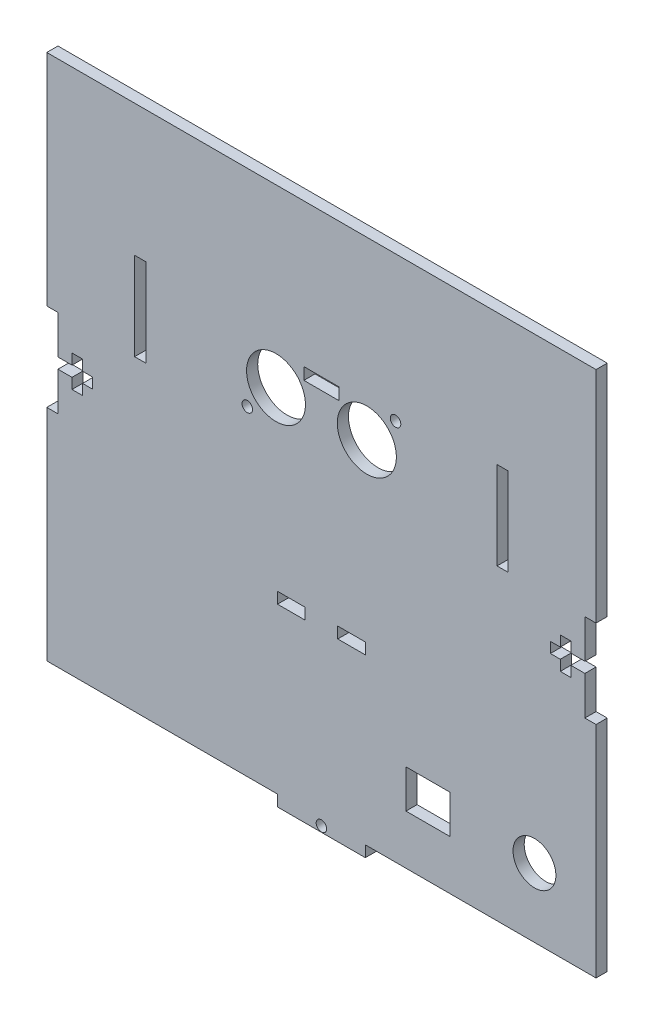
SolidWorks part; units mm, degrees
ref_plane "Front Plane" through (0, 0, 0) normal (0, 0, 1) x (1, 0, 0)
ref_plane "Top Plane" through (0, 0, 0) normal (0, 1, 0) x (1, 0, 0)
ref_plane "Right Plane" through (0, 0, 0) normal (1, 0, 0) x (0, 0, -1)
sketch "Sketch1" plane through (0, 0, 0) normal (0, 0, 1) x (1, 0, 0)
  line L0 (-12.5, 25) -> (12.5, 25) construction
  line L1 (-78.18, 75) -> (78.18, 75)
  line L2 (-78.18, 75) -> (-78.18, 12.5)
  line L3 (-78.18, -75) -> (-12.5, -75)
  line L4 (78.18, 75) -> (78.18, 12.5)
  line L5 (-78.18, 75) -> (78.18, -75) construction
  line L6 (-78.18, -75) -> (78.18, 75) construction
  line L25 (0, 75) -> (0, -75) construction
  line L26 (-100, 0) -> (100, 0) construction
  line L27 (-75, -1.5) -> (-75, -12.5)
  line L28 (-75, 12.5) -> (-78.18, 12.5)
  line L29 (-75, 12.5) -> (-75, 1.5)
  line L30 (-75, -12.5) -> (-78.18, -12.5)
  line L32 (-75, 12.5) -> (-78.18, -12.5) construction
  line L33 (-75, -12.5) -> (-78.18, 12.5) construction
  line L34 (-65.18, 1.5) -> (-68, 1.5)
  line L35 (-65.18, 1.5) -> (-65.18, -1.5)
  line L36 (-65.18, -1.5) -> (-68, -1.5)
  line L38 (-65.18, 1.5) -> (-75, -1.5) construction
  line L39 (-65.18, -1.5) -> (-75, 1.5) construction
  line L44 (-71, 4.5) -> (-68, 4.5)
  line L45 (-71, 4.5) -> (-71, 1.5)
  line L46 (-71, -4.5) -> (-68, -4.5)
  line L47 (-68, 4.5) -> (-68, 1.5)
  line L48 (-71, 4.5) -> (-68, -4.5) construction
  line L49 (-71, -4.5) -> (-68, 4.5) construction
  line L50 (-71, -1.5) -> (-71, -4.5)
  line L51 (-68, -1.5) -> (-68, -4.5)
  line L52 (-71, 1.5) -> (-75, 1.5)
  line L53 (-71, -1.5) -> (-75, -1.5)
  line L54 (65.18, 1.5) -> (68, 1.5)
  line L55 (68, 4.5) -> (68, 1.5)
  line L56 (71, 4.5) -> (68, 4.5)
  line L57 (71, 4.5) -> (71, 1.5)
  line L58 (71, 1.5) -> (75, 1.5)
  line L59 (75, 12.5) -> (75, 1.5)
  line L60 (75, 12.5) -> (78.18, 12.5)
  line L62 (75, -12.5) -> (78.18, -12.5)
  line L63 (75, -1.5) -> (75, -12.5)
  line L64 (71, -1.5) -> (75, -1.5)
  line L65 (71, -1.5) -> (71, -4.5)
  line L66 (71, -4.5) -> (68, -4.5)
  line L67 (68, -1.5) -> (68, -4.5)
  line L68 (65.18, -1.5) -> (68, -1.5)
  line L69 (65.18, 1.5) -> (65.18, -1.5)
  line L70 (-78.18, -12.5) -> (-78.18, -75)
  line L71 (78.18, -12.5) -> (78.18, -75)
  line L72 (0, -78.18) -> (0, -75) construction
  line L74 (12.5, -75) -> (12.5, -78.18)
  line L75 (12.5, -78.18) -> (-12.5, -78.18)
  line L76 (-12.5, -75) -> (-12.5, -78.18)
  line L77 (12.5, -76.59) -> (-12.5, -76.59) construction
  line L78 (12.5, -75) -> (78.18, -75)
  circle A2 centre (0, -76.59) radius 1.5
  point P0 (0, 0)
  point P6 (-51.6, 50)
  point P11 (51.6, 50)
  point P16 (0, 0)
  point P17 (0, -1.6)
  point P27 (0, 25)
  point P30 (-76.59, 0)
  point P35 (-70.09, 0)
  point P40 (-70.09, 0)
  point P41 (-69.5, 0)
  dimension "D13" = 25
  dimension "D23" = 3
  dimension "D1" = 150
  dimension "D2" = 156.36
  dimension "D3" = 9
  dimension "D14" = 50
  dimension "D15" = 25
  dimension "D16" = 13
  dimension "D17" = 3.18
  dimension "D18" = 3
  dimension "D19" = 4
  dimension "D20" = 3
  dimension "D21" = 3.18
  dimension "D22" = 25
extrude "Boss-Extrude1" add sketch "Sketch1" along normal blind 3.18
sketch "Sketch2" plane through (0, 0, 3.18) normal (0, 0, 1) x (1, 0, 0)
  line L0 (30.3478, -50.2) -> (30.3478, -60.7) construction
  line L1 (24.8478, -50.2) -> (35.8478, -50.2) construction
  line L2 (35.8478, -60.7) -> (24.8478, -60.7) construction
  line L3 (24.3478, -55.45) -> (36.3478, -55.45) construction
  line L4 (24.3478, -60.2) -> (24.3478, -50.7) construction
  line L5 (36.3478, -50.7) -> (36.3478, -60.2) construction
  line L7 (24.0625, -49.9909) -> (36.633, -49.9909)
  line L8 (24.0625, -49.9909) -> (24.0625, -60.9091)
  line L9 (24.0625, -60.9091) -> (36.633, -60.9091)
  line L10 (36.633, -49.9909) -> (36.633, -60.9091)
  line L11 (24.0625, -49.9909) -> (36.633, -60.9091) construction
  line L12 (24.0625, -60.9091) -> (36.633, -49.9909) construction
  circle A0 centre (60.6478, -55.45) radius 6.1
  point P12 (30.3478, -55.45)
  dimension "D1" = 12.5705
  dimension "D2" = 10.9182
extrude "Cut-Extrude1" cut sketch "Sketch2" against normal blind 20
sketch "Sketch4" plane through (0, 0, 3.18) normal (0, 0, 1) x (1, 0, 0)
  line L0 (-4.9962, 32.45) -> (-4.9962, 34.25) construction
  line L1 (-4.9962, 34.25) -> (-3.1962, 34.25) construction
  line L2 (3.2038, 30.65) -> (5.0038, 30.65) construction
  line L3 (5.0038, 30.65) -> (5.0038, 32.45) construction
  line L4 (-4.9962, 34.25) -> (-4.9958, 34.15) construction
  line L5 (5.0038, 30.65) -> (5.0035, 30.75) construction
  line L7 (5.0035, 30.75) -> (-4.9958, 30.75)
  line L8 (5.0035, 30.75) -> (5.0035, 34.15)
  line L9 (5.0035, 34.15) -> (-4.9958, 34.15)
  line L10 (-4.9958, 30.75) -> (-4.9958, 34.15)
  circle A0 centre (-12.93, 25) radius 8.385
  circle A1 centre (12.93, 25) radius 8.4104
  arc A2 (-3.1962, 34.25) -> (-3.1962, 30.65) centre (-3.1962, 32.45) ccw construction
  arc A3 (3.2038, 30.65) -> (3.2038, 34.25) centre (3.2038, 32.45) ccw construction
  dimension "D1" = 0.1
  dimension "D2" = 0.1
extrude "Cut-Extrude2" cut sketch "Sketch4" against normal blind 10
sketch "Sketch5" plane through (0, 0, 0) normal (0, 0, -1) x (-1, 0, 0)
  line L0 (12.5, -25) -> (-12.5, -28.18) construction
  line L1 (50, 12.5) -> (53.18, 12.5)
  line L2 (50, 12.5) -> (50, 37.5)
  line L3 (50, 37.5) -> (53.18, 37.5)
  line L4 (53.18, 12.5) -> (53.18, 37.5)
  line L5 (-12.5, -28.18) -> (-4.65, -28.18)
  line L6 (-12.5, -28.18) -> (-12.5, -25)
  line L7 (-12.5, -25) -> (-4.65, -25)
  line L8 (12.5, -28.18) -> (12.5, -25)
  line L9 (-53.18, 12.5) -> (-50, 12.5)
  line L10 (-53.18, 12.5) -> (-53.18, 37.5)
  line L11 (-53.18, 37.5) -> (-50, 37.5)
  line L12 (-50, 12.5) -> (-50, 37.5)
  line L13 (12.5, -28.18) -> (-12.5, -25) construction
  line L14 (4.65, -28.18) -> (12.5, -28.18)
  line L16 (4.65, -25) -> (4.65, -28.18)
  line L18 (-4.65, -25) -> (-4.65, -28.18)
  line L19 (4.65, -25) -> (-4.65, -28.18) construction
  line L20 (4.65, -28.18) -> (-4.65, -25) construction
  line L21 (4.65, -25) -> (12.5, -25)
  point P18 (0, -26.59)
  dimension "D1" = 9.3
extrude "Cut-Extrude3" cut sketch "Sketch5" against normal blind 10
sketch "Sketch8" plane through (0, 0, 0) normal (0, 0, -1) x (-1, 0, 0)
  circle A0 centre (21.1, 16.25) radius 1.5
  circle A1 centre (-21.1, 33.75) radius 1.5
  dimension "D1" = 3
  dimension "D2" = 3
extrude "Cut-Extrude4" cut sketch "Sketch8" against normal blind 10
